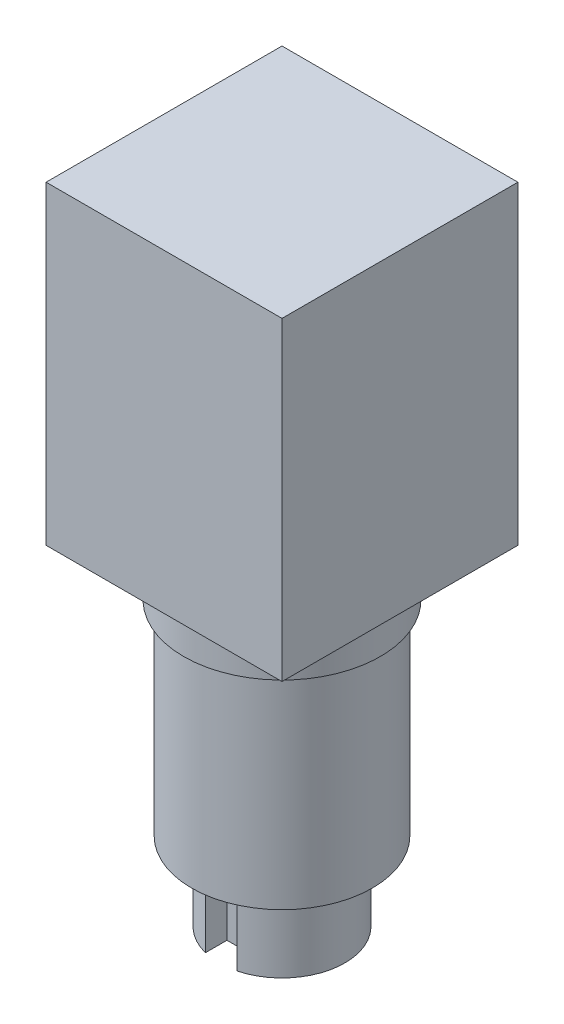
SolidWorks part; units mm, degrees
ref_plane "Front Plane" through (0, 0, 0) normal (0, 0, 1) x (1, 0, 0)
ref_plane "Top Plane" through (0, 0, 0) normal (0, 1, 0) x (1, 0, 0)
ref_plane "Right Plane" through (0, 0, 0) normal (1, 0, 0) x (0, 0, -1)
sketch "Sketch2" plane through (0, 0, 0) normal (0, 1, 0) x (1, 0, 0)
  circle A0 centre (0, 0) radius 4
  dimension "D1" = 8
extrude "Boss-Extrude1" add sketch "Sketch2" along normal blind 5
sketch "Sketch3" plane through (0, 5, 0) normal (0, 1, 0) x (1, 0, 0)
  circle A0 centre (0, 0) radius 5.75
  dimension "D1" = 11.5
extrude "Boss-Extrude2" add sketch "Sketch3" along normal blind 16
sketch "Sketch4" plane through (0, 21, 0) normal (0, 1, 0) x (1, 0, 0)
  line L1 (-7.5, -7.5) -> (7.5, -7.5)
  line L2 (-7.5, -7.5) -> (-7.5, 7.5)
  line L3 (-7.5, 7.5) -> (7.5, 7.5)
  line L4 (7.5, -7.5) -> (7.5, 7.5)
  line L5 (-7.5, -7.5) -> (7.5, 7.5) construction
  line L6 (-7.5, 7.5) -> (7.5, -7.5) construction
  point P0 (0, 0)
  dimension "D1" = 15
extrude "Boss-Extrude3" add sketch "Sketch4" along normal blind 20
sketch "Sketch6" plane through (0, 0, 0) normal (0, -1, 0) x (1, 0, 0)
  circle A0 centre (0, 0) radius 1
  dimension "D1" = 2
sketch "Sketch7" plane through (0, 0, 0) normal (0, -1, 0) x (-1, 0, 0)
  point P0 (0, 0)
hole_wizard "M2x0.4 Tapped Hole1" positions "Sketch7" profile "Sketch9" tap size "M2x0.4" standard "ANSI Metric"
cosmetic thread "Hole Thread1" parameters "D1"=37.78, "D2"=2
sketch "Sketch9" plane through (0, 0, 0) normal (1, 0, 0) x (0, 0, -1)
  line L0 (0, 0) -> (0, 15.4807)
  line L1 (0, 15.4807) -> (0.8, 15)
  line L2 (0.8, 15) -> (0.8, 0.225)
  line L3 (0.8, 0.225) -> (1.025, 0)
  line L5 (1.025, 0) -> (0, 0)
  line L6 (-0.8, 0.225) -> (-1.025, 0) construction
  line L10 (0, 15.4807) -> (-0.8, 15) construction
  line L11 (0, -6.35) -> (0, 107.95) construction
  dimension "Tap Drill Dia." = 1.6
  dimension "Tap Drill Depth" = 15
  dimension "Near C'Sink Dia." = 2.05
  dimension "Near C'Sink Angle" = 90
  dimension "Drill Angle" = 118
sketch "Sketch10" plane through (0, 21, 0) normal (0, -1, 0) x (1, 0, 0)
  circle A0 centre (0, 0) radius 6.25
  dimension "D1" = 12.5
extrude "Boss-Extrude4" add sketch "Sketch10" along normal blind 3
sketch "Sketch11" plane through (0, 0, 0) normal (0, -1, 0) x (1, 0, 0)
  line L1 (-1, 5.5) -> (1, 5.5)
  line L2 (-1, 5.5) -> (-1, 2.5)
  line L3 (-1, 2.5) -> (1, 2.5)
  line L4 (1, 5.5) -> (1, 2.5)
  line L5 (-1, 5.5) -> (1, 2.5) construction
  line L6 (-1, 2.5) -> (1, 5.5) construction
  circle A2 centre (0, 0) radius 4 construction
  point P0 (0, 4)
  dimension "D1" = 2
  dimension "D2" = 1.5
extrude "Cut-Extrude2" cut sketch "Sketch11" against normal up to surface (5 mm away) up to face at (0, 5, 4)
